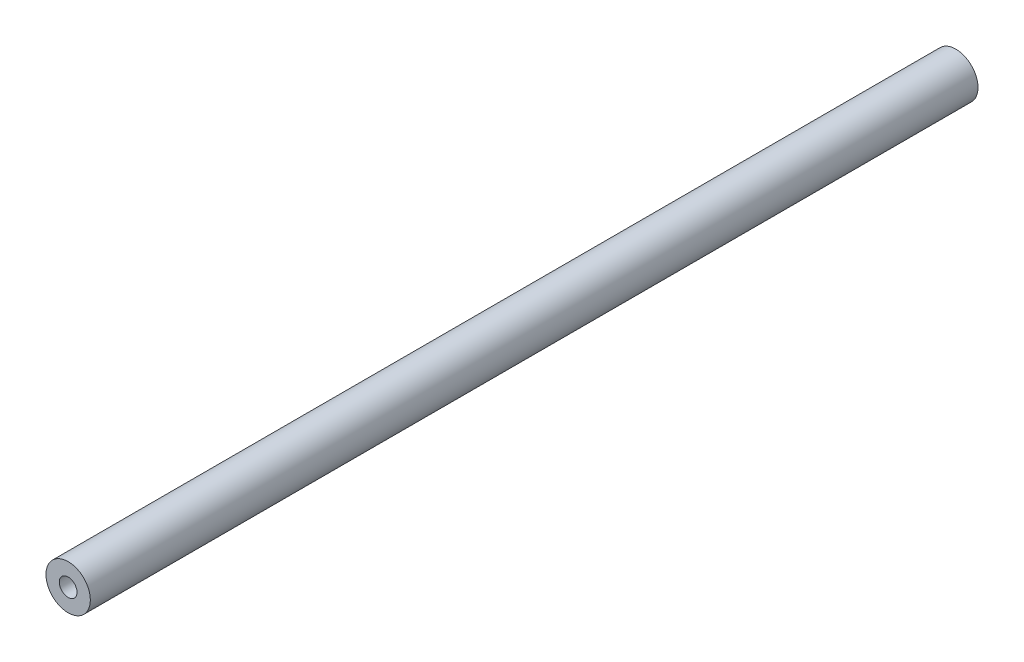
SolidWorks part; units mm, degrees
ref_plane "Front Plane" through (0, 0, 0) normal (0, 0, 1) x (1, 0, 0)
ref_plane "Top Plane" through (0, 0, 0) normal (0, 1, 0) x (1, 0, 0)
ref_plane "Right Plane" through (0, 0, 0) normal (1, 0, 0) x (0, 0, -1)
sketch "Sketch1" plane through (0, 0, 0) normal (0, 0, 1) x (1, 0, 0)
  circle A0 centre (0, 0) radius 7.5
  dimension "D1" = 15
extrude "Boss-Extrude1" add sketch "Sketch1" along normal blind 300
sketch "Sketch2" plane through (0, 0, 0) normal (0, 0, -1) x (-1, 0, 0)
  circle A0 centre (0, 0) radius 3
  dimension "D1" = 6
extrude "Cut-Extrude1" cut sketch "Sketch2" against normal blind 30
sketch "Sketch3" plane through (0, 0, 300) normal (0, 0, 1) x (1, 0, 0)
  circle A0 centre (0, 0) radius 3
  dimension "D1" = 6
extrude "Cut-Extrude2" cut sketch "Sketch3" against normal blind 30
